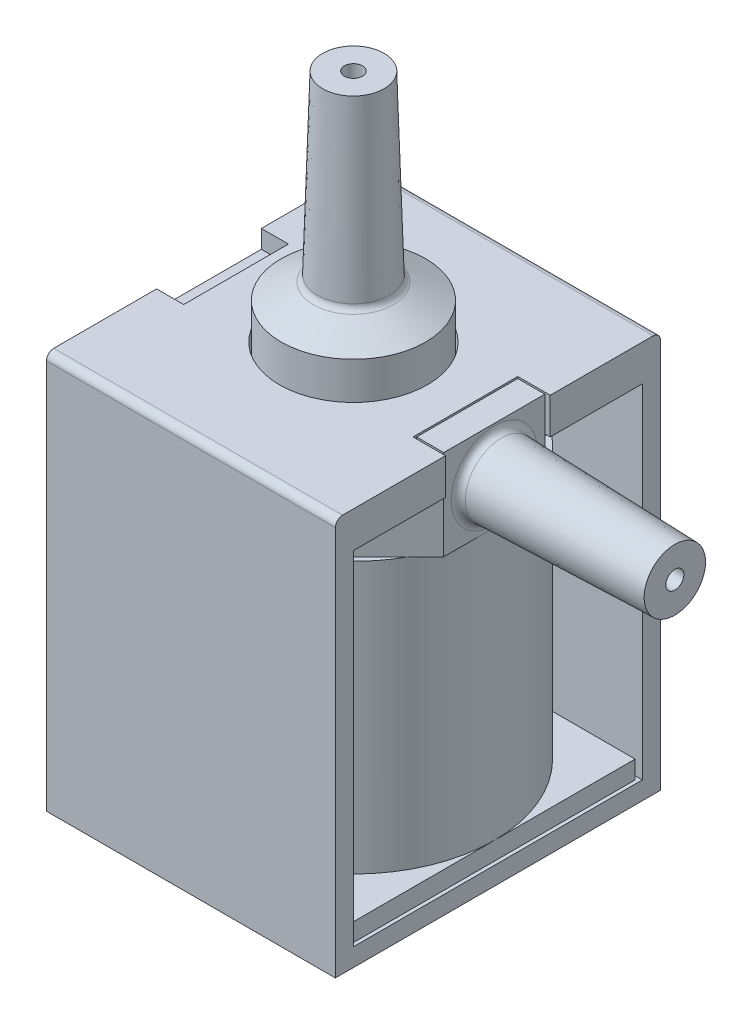
SolidWorks part; units mm, degrees
ref_plane "前视基准面" through (0, 0, 0) normal (0, 0, 1) x (1, 0, 0)
ref_plane "上视基准面" through (0, 0, 0) normal (0, 1, 0) x (1, 0, 0)
ref_plane "右视基准面" through (0, 0, 0) normal (1, 0, 0) x (0, 0, -1)
sketch "草图1" plane through (0, 0, 0) normal (0, 1, 0) x (1, 0, 0)
  line L0 (8, 9) -> (-8, 9)
  line L1 (8, 9) -> (8, -9)
  line L2 (-8, 9) -> (-8, -9)
  line L3 (8, -9) -> (-8, -9)
  line L4 (8, 9) -> (-8, -9) construction
  line L5 (-8, 9) -> (8, -9) construction
  point P1 (0, 0)
  dimension "D1" = 18
  dimension "D2" = 16
extrude "凸台-拉伸1" add sketch "草图1" along normal blind 1
sketch "草图2" plane through (0, 1, 0) normal (0, 1, 0) x (1, 0, 0)
  line L0 (7.8, 7.8) -> (-7.8, 7.8)
  line L1 (7.8, 7.8) -> (7.8, -7.8)
  line L2 (-7.8, 7.8) -> (-7.8, -7.8)
  line L3 (7.8, -7.8) -> (-7.8, -7.8)
  line L4 (7.8, 7.8) -> (-7.8, -7.8) construction
  line L5 (-7.8, 7.8) -> (7.8, -7.8) construction
  dimension "D1" = 15.6
  dimension "D2" = 15.6
extrude "凸台-拉伸2" add sketch "草图2" along normal blind 1
sketch "草图3" plane through (0, 2, 0) normal (0, 1, 0) x (1, 0, 0)
  circle A0 centre (0, 0) radius 7.8
  dimension "D1" = 15.6
extrude "凸台-拉伸3" add sketch "草图3" along normal blind 15
sketch "草图4" plane through (0, 17, 0) normal (0, 1, 0) x (1, 0, 0)
  line L0 (0, 0) -> (0, 7.8) construction
  line L1 (7.8, 7.8) -> (-7.8, 7.8) construction
  line L2 (-4.8, 7.8) -> (4.8, 7.8)
  line L3 (7.8, 7.8) -> (0, 7.8) construction
  line L4 (4.8, 7.8) -> (4.8, 5.8)
  line L5 (4.8, 5.8) -> (7.8, 2.8)
  line L6 (7.8, 0) -> (7.8, 7.8) construction
  line L7 (7.8, 2.8) -> (7.8, -2.8)
  line L8 (7.8, -7.8) -> (7.8, 0) construction
  line L9 (7.8, -2.8) -> (4.8, -5.8)
  line L10 (4.8, -5.8) -> (4.8, -7.8)
  line L11 (-7.8, -7.8) -> (7.8, -7.8) construction
  line L12 (4.8, -7.8) -> (-4.8, -7.8)
  line L14 (-4.8, -5.8) -> (-4.8, -7.8)
  line L15 (-7.8, -2.8) -> (-4.8, -5.8)
  line L16 (-7.8, 2.8) -> (-7.8, -2.8)
  line L17 (-4.8, 5.8) -> (-7.8, 2.8)
  line L18 (-4.8, 7.8) -> (-4.8, 5.8)
  point P21 (0, -7.8)
  dimension "D1" = 2
  dimension "D2" = 3
  dimension "D3" = 3
  dimension "D4" = 3
  dimension "D5" = 2
  dimension "D6" = 3
extrude "凸台-拉伸4" add sketch "草图4" along normal blind 3
sketch "草图5" plane through (0, 20, 0) normal (0, 1, 0) x (1, 0, 0)
  circle A0 centre (0, 0) radius 4
  dimension "D1" = 8
extrude "凸台-拉伸5" add sketch "草图5" along normal blind 4
sketch "草图6" plane through (0, 0, 0) normal (0, 0, 1) x (1, 0, 0)
  line L0 (0, 24) -> (4, 24)
  line L1 (4, 24) -> (-4, 24) construction
  line L2 (4, 24) -> (2, 25)
  line L3 (2, 25) -> (1.7, 35)
  line L4 (1.7, 35) -> (0, 35)
  line L5 (0, 35) -> (0, 24)
  dimension "D1" = 11
  dimension "D2" = 4
  dimension "D3" = 2
  dimension "D4" = 1
  dimension "D5" = 1.7
revolve "旋转1" add sketch "草图6" angle 360 about L5
sketch "草图7" plane through (0, 35, 0) normal (0, 1, 0) x (1, 0, 0)
  circle A0 centre (0, 0) radius 0.5
  dimension "D1" = 1
extrude "切除-拉伸1" cut sketch "草图7" against normal blind 15
sketch "草图8" plane through (0, 20, 0) normal (0, 1, 0) x (1, 0, 0)
  line L0 (7.8, 2.8) -> (7.8, -2.8)
  line L1 (7.8, -2.8) -> (6.3, -2.8)
  line L2 (6.3, -2.8) -> (6.3, 2.8)
  line L3 (6.3, 2.8) -> (7.8, 2.8)
  dimension "D1" = 1.5
extrude "凸台-拉伸6" add sketch "草图8" along normal blind 2
sketch "草图9" plane through (7.8, 0, 0) normal (1, 0, 0) x (0, 0, -1)
  line L0 (0, 22) -> (0, 19.5) construction
  line L2 (-2.8, 22) -> (2.8, 22) construction
  line L3 (0, 19.5) -> (-2, 19.5) construction
  circle A0 centre (0, 19.5) radius 2
  dimension "D2" = 4
  dimension "D1" = 2.5
ref_plane "基准面1" through (17.8, 0, 0) normal (1, 0, 0) x (0, 0, -1)
sketch "草图10" plane through (17.8, 0, 0) normal (1, 0, 0) x (0, 0, -1)
  line L0 (0, 19.5) -> (-1.7, 19.5) construction
  circle A0 centre (0, 19.5) radius 1.7
  dimension "D1" = 3.4
loft "放样1" add profiles "草图9", "草图10"
sketch "草图11" plane through (17.8, 0, 0) normal (1, 0, 0) x (0, 0, -1)
  circle A0 centre (0, 19.5) radius 0.5
  dimension "D1" = 1
extrude "切除-拉伸2" cut sketch "草图11" against normal blind 11
sketch "草图12" plane through (0, 1, 0) normal (0, 1, 0) x (1, 0, 0)
  line L0 (8, -9) -> (8, 9) construction
  line L1 (-8, 9) -> (8, 9)
  line L2 (-8, 9) -> (-8, 8)
  line L3 (-8, 8) -> (8, 8)
  line L4 (8, 9) -> (8, 8)
  line L6 (-8, -9) -> (8, -9)
  line L7 (-8, -9) -> (-8, -8)
  line L8 (-8, -8) -> (8, -8)
  line L9 (8, -9) -> (8, -8)
  dimension "D1" = 1
  dimension "D2" = 1
extrude "凸台-拉伸7" add sketch "草图12" along normal blind 19
sketch "草图13" plane through (0, 20, 0) normal (0, 1, 0) x (1, 0, 0)
  line L0 (8, 2.9) -> (6.2, 2.9)
  line L1 (-8, 9) -> (8, 9)
  line L2 (-8, 9) -> (-8, -9)
  line L3 (-8, -9) -> (8, -9)
  line L4 (8, 9) -> (8, 2.9)
  line L5 (6.2, 2.9) -> (6.2, -2.9)
  line L6 (6.2, -2.9) -> (8, -2.9)
  line L7 (7.8, 2.8) -> (6.3, 2.8) construction
  line L8 (6.3, 2.8) -> (6.3, -2.8) construction
  line L9 (6.3, -2.8) -> (7.8, -2.8) construction
  line L10 (8, -2.9) -> (8, -9)
  circle A0 centre (0, 0) radius 4.1
  dimension "D1" = 8.2
  dimension "D2" = 0.1
  dimension "D3" = 0.1
  dimension "D4" = 0.1
extrude "凸台-拉伸8" add sketch "草图13" along normal blind 2
sketch "草图14" plane through (0, 22, 0) normal (0, 1, 0) x (1, 0, 0)
  line L0 (6.2, 2.9) -> (-8, 2.9) construction
  line L1 (-8, 9) -> (-8, -9) construction
  line L2 (6.2, -2.9) -> (-8, -2.9) construction
  line L4 (-8, 2.9) -> (-6.5, 2.9)
  line L5 (-8, 2.9) -> (-8, -2.9)
  line L6 (-8, -2.9) -> (-6.5, -2.9)
  line L7 (-6.5, 2.9) -> (-6.5, -2.9)
  dimension "D1" = 1.5
extrude "切除-拉伸3" cut sketch "草图14" against normal blind 1
fillet "圆角1" radius 0.4 2 edges at (-2, 25, 0) (7.8, 19.5, -2)
fillet "圆角2" radius 0.4 2 edges at (0, 22, -9) (0, 22, 9)
